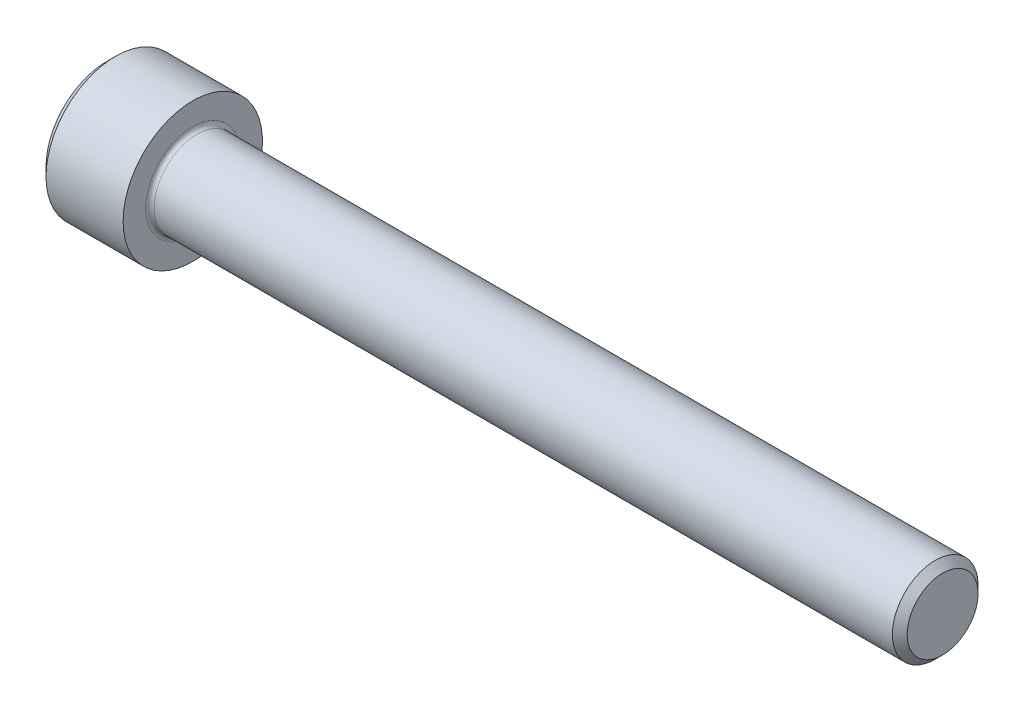
SolidWorks part; units mm, degrees
revolve "Base-Revolve" add sketch "BodySke"
sketch "BodySke" plane through (0, 0, 0) normal (0, 0, 1) x (1, 0, 0)
  line L0 (0, 0) -> (0, 5.7)
  line L1 (0.8, 6.5) -> (8, 6.5)
  line L2 (8, 6.5) -> (8, 4)
  line L3 (8, 4) -> (77.3095, 4)
  line L4 (78, 3.3095) -> (78, 0)
  line L5 (78, 0) -> (0, 0)
  line L6 (-31.75, 0) -> (127, 0) construction
  line L7 (0, 5.7) -> (0.8, 6.5)
  line L8 (78, 3.3095) -> (77.3095, 4)
  line L9 (0, -5.7) -> (0.8, -6.5) construction
  line L10 (78, -3.3095) -> (77.3095, -4) construction
  line L11 (9.25, 2.4825) -> (9.25, -3.8675) construction
  line L12 (50, 2.4825) -> (50, -3.8675) construction
  line L13 (28, 2.4825) -> (28, -3.8675) construction
  dimension "Diameter" = 8
  dimension "Head_ht" = 8
  dimension "Length" = 70
  dimension "Body_ch_ang" = 45
  dimension "Head_dia" = 13
  dimension "Head_ch_ang" = 45
  dimension "Minor_dia" = 6.619
  dimension "Advance" = 1.25
  dimension "Thread_nom" = 28
  dimension "Thread_length" = 50
  dimension "Head_ch_ht" = 0.8
cosmetic thread "ThreadCosmetic" [suppressed]
fillet "Fillet1" radius 0.4 1 edges at (8, 0, 4)
ref_plane "Plane1" through (0, 0, 0) normal (0, 0, 1) x (1, 0, 0)
ref_plane "Plane2" through (0, 0, 0) normal (0, 1, 0) x (1, 0, 0)
ref_plane "Plane3" through (0, 0, 0) normal (1, 0, 0) x (0, 0, -1)
other "Configuration Table"
sketch "Sketch2" plane through (0, 0, 0) normal (0, 0, 1) x (1, 0, 0)
  line L0 (0, 3.0475) -> (4, 3.0475)
  line L1 (4, 3.0475) -> (5.7595, 0)
  line L2 (-31.75, 0) -> (127, 0) construction
  line L3 (5.7595, 0) -> (0, 0)
  line L4 (0, 0) -> (0, 3.0475)
  line L5 (0, 5.7) -> (0, -5.7) construction
  line L6 (0, 0) -> (47.625, 0) construction
  line L7 (8, -6.5) -> (8, 6.5) construction
  dimension "D1" = 3.0475
  dimension "D2" = 60
revolve "Hex-PreBroach" cut sketch "Sketch2" angle 360 about L6
sketch "Sketch3" plane through (0, 0, 0) normal (-1, 0, 0) x (0, 0.5, 0.866)
  line L0 (1.7595, 3.0475) -> (-1.7595, 3.0475)
  line L1 (-1.7595, 3.0475) -> (-3.5189, 0)
  line L2 (1.7595, 3.0475) -> (3.5189, 0)
  line L3 (1.7595, -3.0475) -> (3.5189, 0)
  line L4 (1.7595, -3.0475) -> (-1.7595, -3.0475)
  line L5 (-1.7595, -3.0475) -> (-3.5189, 0)
  dimension "D1" = 3.0475
  dimension "D2" = 3.0475
  dimension "Hex_size" = 6.095
extrude "Hex" cut sketch "Sketch3" against normal blind 4
sketch "Sketch4" plane through (0, 0, 0) normal (-1, 0, 0) x (0, 0, 1)
  line L0 (0, 0) -> (3.7846, 0)
  line L1 (0, 0) -> (6.1484, 3.5498) construction
  line L2 (0, 0) -> (1.8923, 3.2776)
  line L3 (3.1235, 0.8061) -> (3.6229, 1.0945)
  line L4 (2.2599, 2.3019) -> (2.7593, 2.5903)
  arc A0 (3.1235, 0.8061) -> (2.2599, 2.3019) centre (0, 0) ccw
  arc A1 (3.7846, 0) -> (3.6229, 1.0945) centre (0, 0) ccw
  arc A2 (1.8923, 3.2776) -> (2.7593, 2.5903) centre (0, 0) cw
  dimension "D2" = 60
  dimension "D1" = 30
  dimension "Spline_p_dim" = 1.7272
  dimension "D3" = 0.8636
extrude "Spline" [suppressed] cut sketch "Sketch4" against normal blind 4
pattern_circular "CirPattern1" [suppressed] count 6 every 60
sketch "Sketch5" plane through (0, 0, 0) normal (0, 0, 1) x (1, 0, 0)
  line L0 (-31.75, 0) -> (127, 0) construction
  line L2 (0, 5.7) -> (0, -5.7) construction
  circle A0 centre (2.7, 0) radius 0.675
  dimension "Drilled_hole_dia" = 1.35
  dimension "Drilled_hole_loc" = 2.7
extrude "Hole" [suppressed] cut sketch "Sketch5" against normal through all and the other way through all
pattern_circular "Drilled-4" [suppressed] count 2 every 60
pattern_circular "Drilled-6" [suppressed] count 3 every 60
sketch "ThdSchSke" plane through (0, 0, 0) normal (0, 0, 1) x (1, 0, 0)
  line L0 (50, -3.3095) -> (49.5165, -4)
  line L1 (50, -3.3095) -> (50.4835, -4)
  line L2 (50.4835, -4) -> (50.4835, -5)
  line L3 (-3.175, 0) -> (5.1513, 0) construction
  line L5 (50.4835, -5) -> (49.5165, -5)
  line L6 (49.5165, -5) -> (49.5165, -4)
  line L7 (0, 5.7) -> (0, -5.7) construction
  dimension "Thread_minor" = 6.619
  dimension "Diameter" = 8
  dimension "Start" = 50
revolve "ThreadSchematic" [suppressed] cut sketch "ThdSchSke" angle 360 about L3
pattern_linear "ThdSchPat" [suppressed]
equation "\"D2@Sketch3\" = \"Hex_size@Sketch3\" / 2"
equation "\"D1@Sketch3\" = \"Hex_size@Sketch3\" / 2"
equation "\"D1@Sketch2\" = \"Hex_size@Sketch3\" / 2"
equation "\"D3@Sketch4\" = \"Spline_p_dim@Sketch4\" / 2"
equation "\"Thread_minor@ThreadCosmetic\"  =  \"Minor_dia@BodySke\""
equation "\"D2@CirPattern1\" = 360 / \"Num_teeth@CirPattern1\""
equation "\"Wall_thickness@Sketch2\" = \"Head_ht@BodySke\" - \"Key_eng@Hex\""
equation "\"Thread_length@ThreadCosmetic\" = ((sgn( (\"Length@BodySke\" - \"Advance@BodySke\" ) - \"Thread_nom@BodySke\" )-1)*( (\"Length@BodySke\" - \"Advance@BodySke\" ) - \"Thread_nom@BodySke\" ))/-2+ \"Thread_nom@BodySke\""
equation "\"Thread_minor@ThdSchSke\" = \"Minor_dia@BodySke\""
equation "\"Diameter@ThdSchSke\" = \"Diameter@BodySke\""
equation "\"Overcut@ThdSchSke\" = \"Diameter@BodySke\" * 1.25"
equation "\"Start@ThdSchSke\" = \"Head_ht@BodySke\" + \"Length@BodySke\" - \"Thread_length@ThreadCosmetic\"  '---Non-countersunk---"
equation "\"Num_threads@ThdSchPat\" = int( \"Thread_length@ThreadCosmetic\" / \"Advance@BodySke\" + 0.999 )  + 1"
equation "\"Advance@ThdSchPat\" = \"Thread_length@ThreadCosmetic\" /  (\"Num_threads@ThdSchPat\" - 1) 'relax it"
equation "\"Num_threads@ThdSchPat\" = \"Num_threads@ThdSchPat\" - sgn( \"Num_threads@ThdSchPat\" - 1) '---chamfered tips only---"
